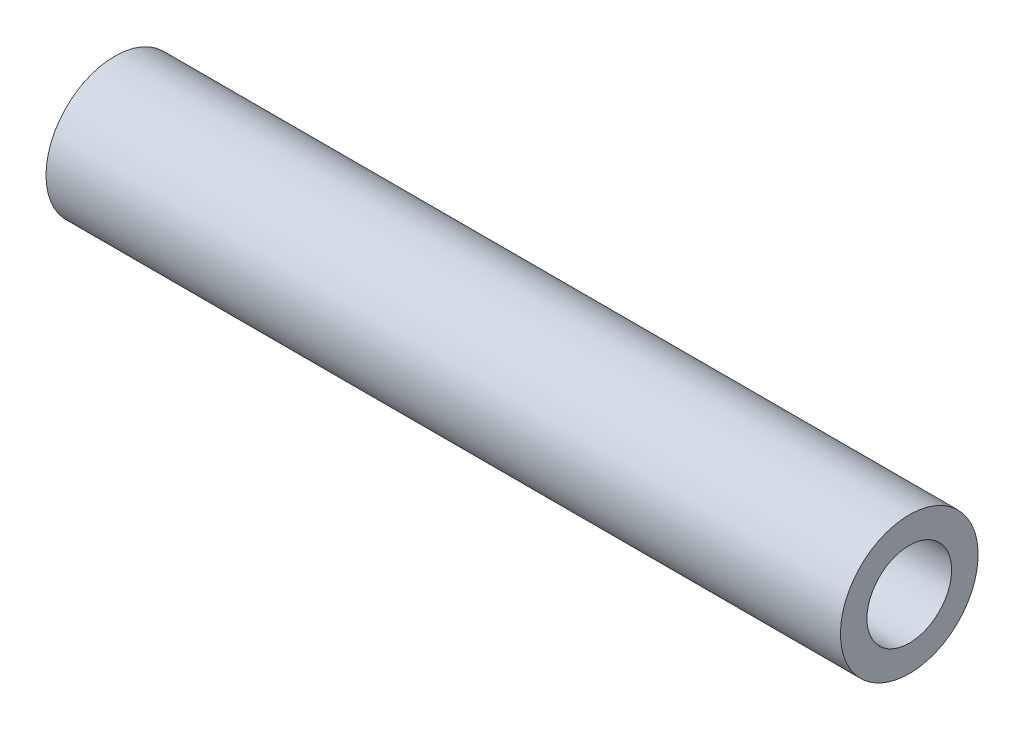
SolidWorks part; units mm, degrees
ref_plane "Front Plane" through (0, 0, 0) normal (0, 0, 1) x (1, 0, 0)
ref_plane "Top Plane" through (0, 0, 0) normal (0, 1, 0) x (1, 0, 0)
ref_plane "Right Plane" through (0, 0, 0) normal (1, 0, 0) x (0, 0, -1)
sketch "Sketch1" plane through (0, 0, 0) normal (0, 0, 1) x (1, 0, 0)
  line L0 (-101.3955, 0) -> (101.3955, 0) construction
  line L1 (-75, 8) -> (75, 8)
  line L2 (-75, 8) -> (-75, 13)
  line L3 (-75, 13) -> (75, 13)
  line L4 (75, 13) -> (75, 8)
  line L5 (0, 0) -> (0, 48.079) construction
  point P4 (0, 0)
  point P11 (0, 8)
  dimension "D1" = 202.7911
  dimension "D2" = 8
  dimension "D3" = 5
  dimension "D4" = 150
revolve "Revolve1" add sketch "Sketch1" angle 360 about L0
